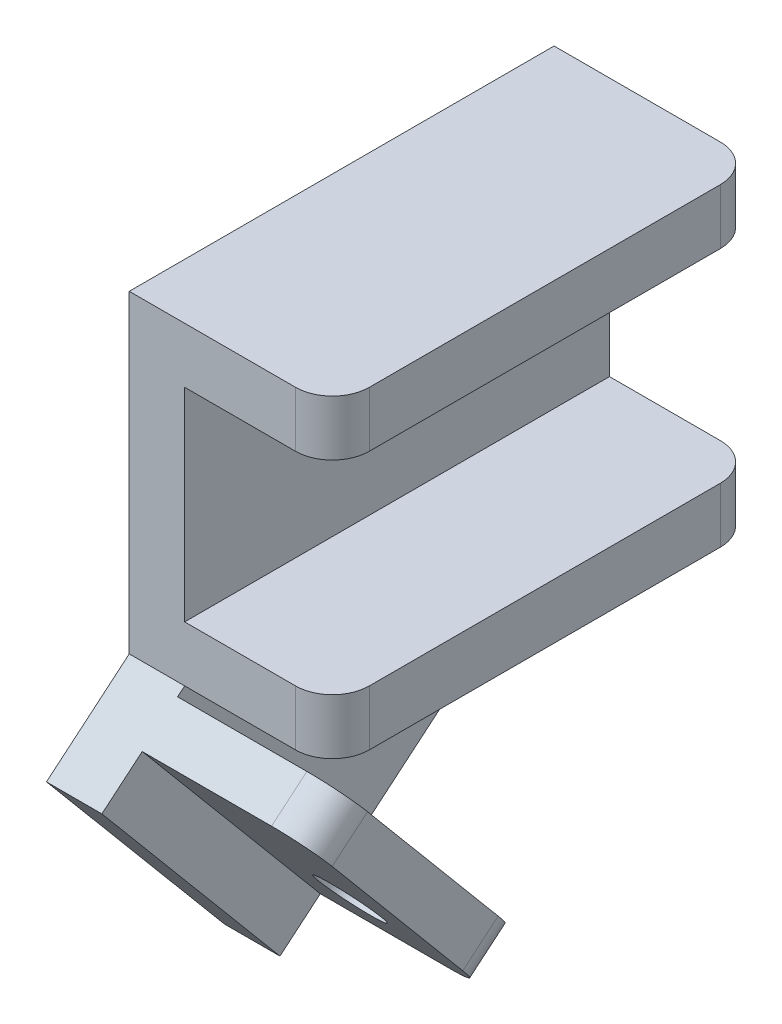
SolidWorks part; units mm, degrees
ref_plane "Front" through (0, 0, 0) normal (0, 0, 1) x (1, 0, 0)
ref_plane "Top" through (0, 0, 0) normal (0, 1, 0) x (1, 0, 0)
ref_plane "Right" through (0, 0, 0) normal (1, 0, 0) x (0, 0, -1)
sketch "Sketch1" plane through (0, 0, 0) normal (0, 0, 1) x (1, 0, 0)
  line L0 (0, 0) -> (-8, 0)
  line L1 (-8, 0) -> (-8, -11)
  line L2 (-8, -11) -> (0, -11)
  line L3 (0, 3) -> (-11, 3)
  line L4 (-11, 3) -> (-11, -14)
  line L5 (-11, -14) -> (0, -14)
  line L6 (0, 0) -> (0, 3)
  line L7 (0, -11) -> (0, -14)
  dimension "D1" = 8
  dimension "D2" = 11
  dimension "D3" = 3
extrude "Boss-Extrude1" add sketch "Sketch1" along normal blind 23 contours L3 L4 L5 L7 L2 L1 L0 L6
sketch "Sketch2" plane through (-11, 0, 0) normal (-1, 0, 0) x (0, 0, 1)
  line L0 (23, -14) -> (0, -14)
  line L1 (0, -14) -> (-0.1388, -14.1654)
  line L2 (-0.1388, -14.1654) -> (15.6563, -27.419)
  line L3 (23, 3) -> (23, -14) construction
  line L4 (23, -14) -> (25.2981, -15.9284)
  line L5 (25.2981, -15.9284) -> (15.6563, -27.419)
  dimension "D1" = 15
  dimension "D2" = 3
  dimension "D3" = 50
extrude "Boss-Extrude3" add sketch "Sketch2" against normal blind 3 contours L2 L5 L4 L0 L1
sketch "Sketch3" plane through (-8, 0, 0) normal (1, 0, 0) x (0, 0, -1)
  line L0 (-25.2981, -15.9284) -> (-23.383, -14.3214)
  line L1 (-23, -14) -> (-25.2981, -15.9284) construction
  line L2 (-23.383, -14.3214) -> (-13.7412, -25.8121)
  line L3 (0.1388, -14.1654) -> (-15.6563, -27.419) construction
  line L4 (-13.7412, -25.8121) -> (-15.6563, -27.419)
  line L5 (-15.6563, -27.419) -> (-25.2981, -15.9284)
  dimension "D1" = 2.5
extrude "Boss-Extrude4" add sketch "Sketch3" along normal blind 9
sketch "Sketch4" plane through (0, -17.4311, 20.7736) normal (0, 0.6428, -0.766) x (-1, 0, 0)
  line L0 (3.5, -10.9405) -> (3.5, -6.4405) construction
  line L1 (-1, -10.9405) -> (8, -10.9405) construction
  circle A0 centre (3.5, -6.4405) radius 1.7
  dimension "D1" = 3.4
  dimension "D2" = 4.5
extrude "Cut-Extrude1" cut sketch "Sketch4" against normal through all
sketch "Sketch5" plane through (0, -19.0381, 22.6887) normal (0, -0.6428, 0.766) x (1, 0, 0)
  line L0 (1, -10.9405) -> (-11, -10.9405) construction
  line L1 (-11, 4.0595) -> (-8, 4.0595)
  line L2 (-11, 4.0595) -> (-11, -10.9405)
  line L3 (-11, -10.9405) -> (-8, -10.9405)
  line L4 (-8, 4.0595) -> (-8, -10.9405)
  line L5 (-8, 14.7841) -> (-8, 6.3576) construction
extrude "Boss-Extrude5" add sketch "Sketch5" along normal blind 2.85
sketch "Sketch6" plane through (-11, 0, 0) normal (-1, 0, 0) x (0, 0, 1)
  line L0 (6, 3) -> (6, -5) construction
  line L2 (0, 3) -> (0, -14) construction
  circle A0 centre (6, -5) radius 1.6
  dimension "D1" = 3.2
  dimension "D2" = 8
  dimension "D3" = 6
extrude "Cut-Extrude2" cut sketch "Sketch6" against normal through all
fillet "Fillet1" radius 2 6 edges at (1, -15.1249, 24.3406) (1, -26.6155, 14.6988) (0, -12.5, 0) (0, 1.5, 0) (0, 1.5, 23) (0, -12.5, 23)
